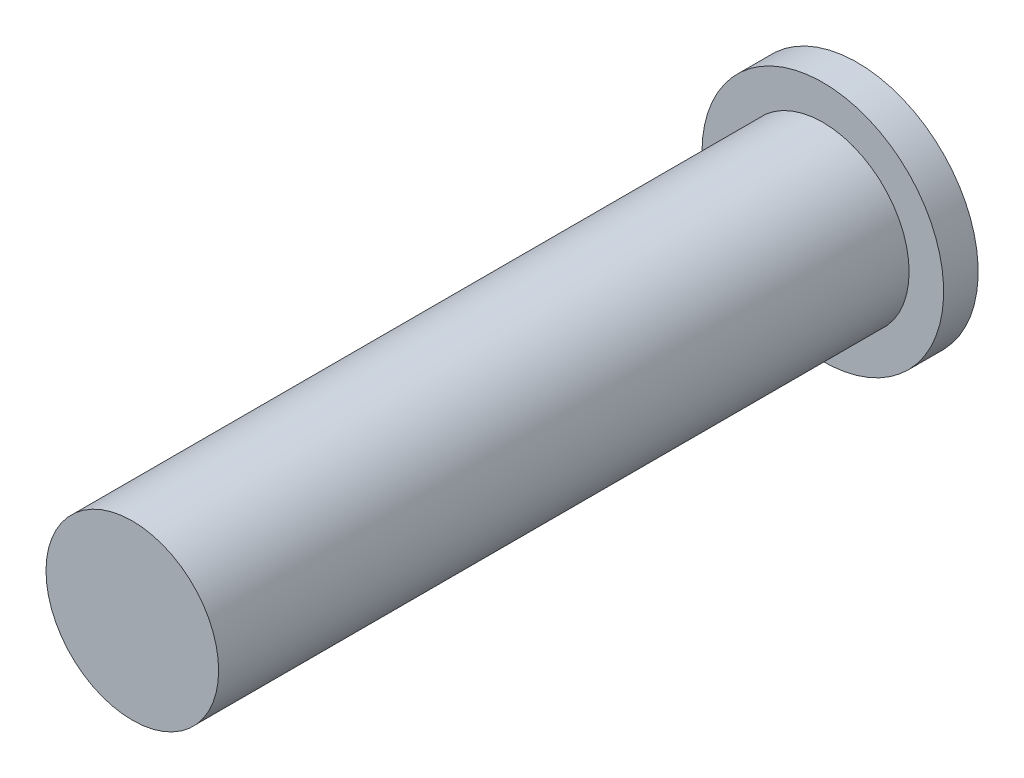
SolidWorks part; units mm, degrees
ref_plane "Front Plane" through (0, 0, 0) normal (0, 0, 1) x (1, 0, 0)
ref_plane "Top Plane" through (0, 0, 0) normal (0, 1, 0) x (1, 0, 0)
ref_plane "Right Plane" through (0, 0, 0) normal (1, 0, 0) x (0, 0, -1)
sketch "Sketch1" plane through (0, 0, 0) normal (0, 0, 1) x (1, 0, 0)
  circle A0 centre (0, 0) radius 5
  dimension "D1" = 10
extrude "Boss-Extrude1" add sketch "Sketch1" along normal blind 40
sketch "Sketch2" plane through (0, 0, 0) normal (0, 0, -1) x (-1, 0, 0)
  circle A1 centre (0, 0) radius 7
  circle A2 centre (0, 0) radius 5
  circle A3 centre (0, 0) radius 5 construction
  dimension "D1" = 0
  dimension "D2" = 2
extrude "Boss-Extrude2" add sketch "Sketch2" along normal blind 2
